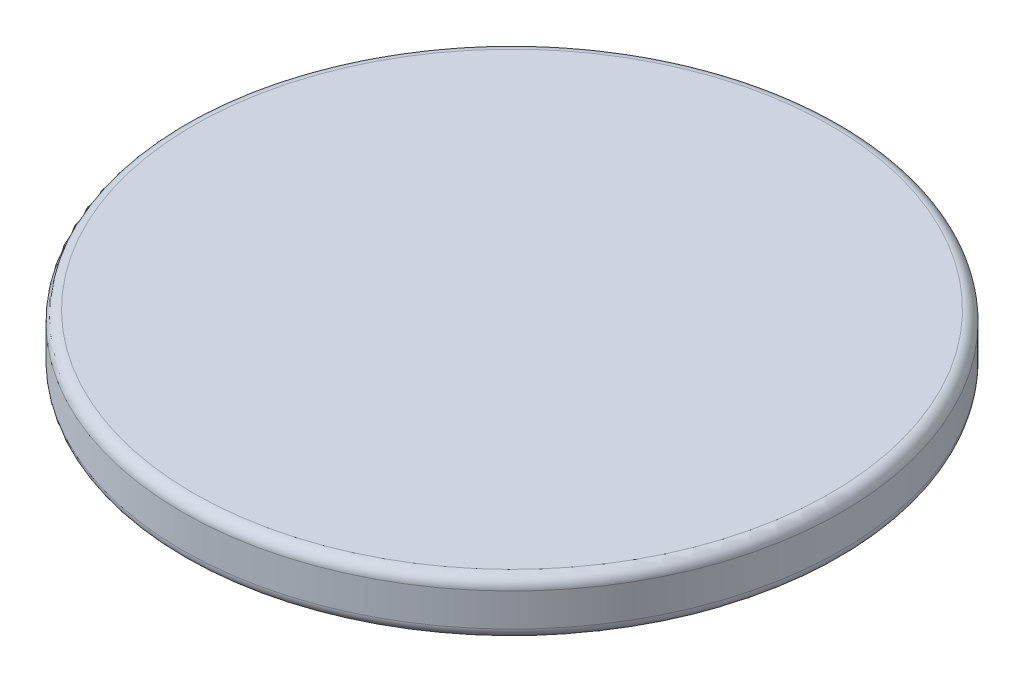
SolidWorks part; units mm, degrees
ref_plane "Front" through (0, 0, 0) normal (0, 0, 1) x (1, 0, 0)
ref_plane "Top" through (0, 0, 0) normal (0, 1, 0) x (1, 0, 0)
ref_plane "Right" through (0, 0, 0) normal (1, 0, 0) x (0, 0, -1)
sketch "Sketch1" plane through (0, 0, 0) normal (0, 1, 0) x (1, 0, 0)
  circle A0 centre (0, 0) radius 228.6
extrude "Boss-Extrude1" add sketch "Sketch1" along normal blind 38.1
fillet "Fillet1" radius 7.62 2 edges at (0, 0, 228.6) (0, 38.1, 228.6)
